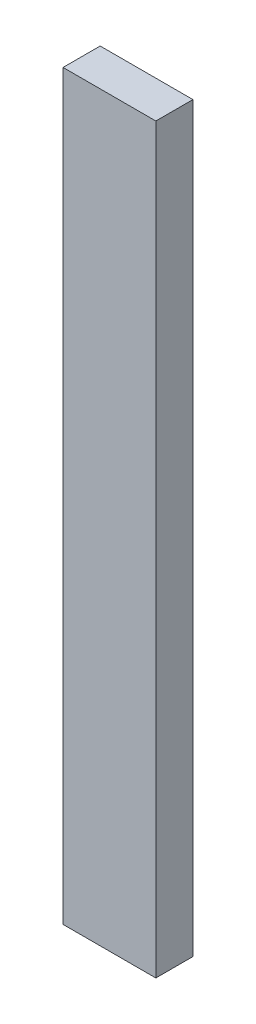
SolidWorks part; units mm, degrees
ref_plane "前视基准面" through (0, 0, 0) normal (0, 0, 1) x (1, 0, 0)
ref_plane "上视基准面" through (0, 0, 0) normal (0, 1, 0) x (1, 0, 0)
ref_plane "右视基准面" through (0, 0, 0) normal (1, 0, 0) x (0, 0, -1)
sketch "草图1" plane through (0, 0, 0) normal (0, 1, 0) x (1, 0, 0)
  line L1 (0, 0) -> (25, 0)
  line L2 (0, 0) -> (0, 10)
  line L3 (0, 10) -> (25, 10)
  line L4 (25, 0) -> (25, 10)
  dimension "D1" = 10
  dimension "D2" = 25
extrude "凸台-拉伸1" add sketch "草图1" along normal blind 200
